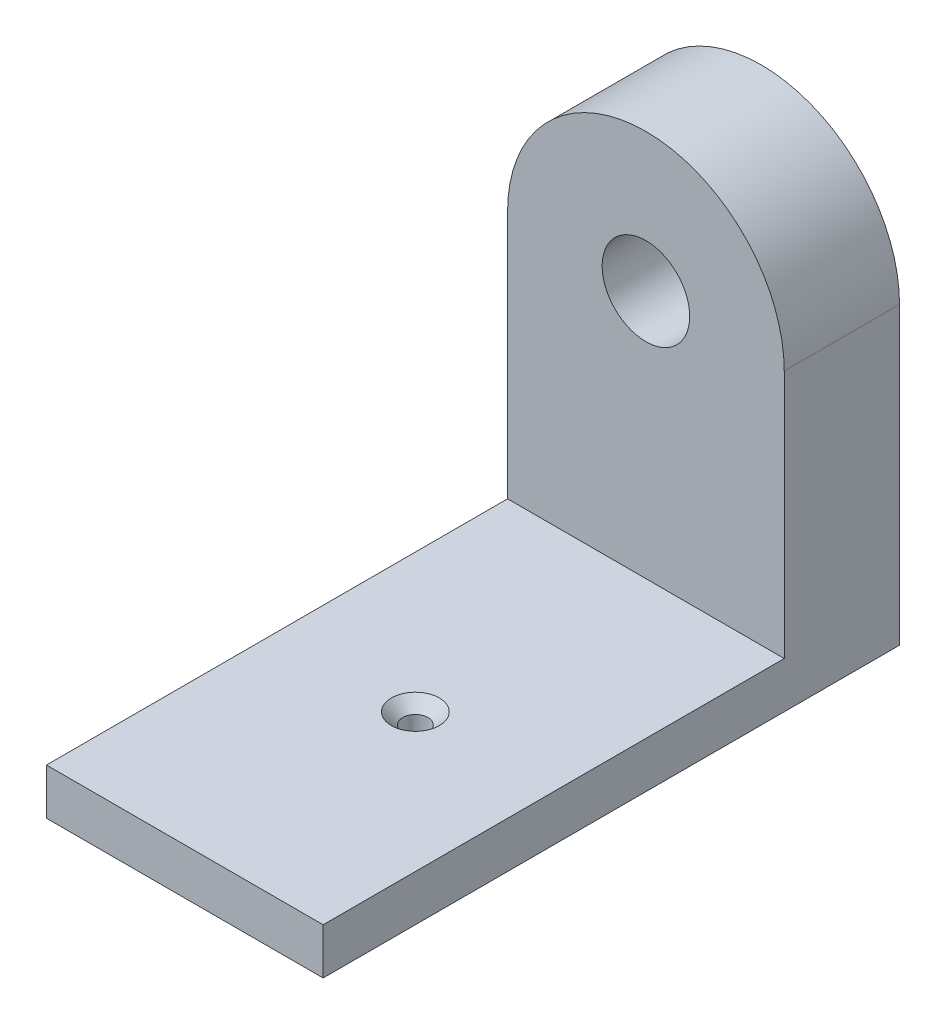
SolidWorks part; units mm, degrees
ref_plane "Front Plane" through (0, 0, 0) normal (0, 0, 1) x (1, 0, 0)
ref_plane "Top Plane" through (0, 0, 0) normal (0, 1, 0) x (1, 0, 0)
ref_plane "Right Plane" through (0, 0, 0) normal (1, 0, 0) x (0, 0, -1)
sketch "Sketch1" plane through (0, 0, 0) normal (0, 1, 0) x (1, 0, 0)
  line L1 (0, 0) -> (60, 0)
  line L2 (0, 0) -> (0, 125)
  line L3 (0, 125) -> (60, 125)
  line L4 (60, 0) -> (60, 125)
  dimension "D1" = 125
  dimension "D2" = 60
extrude "Boss-Extrude1" add sketch "Sketch1" along normal blind 10
sketch "Sketch2" plane through (0, 0, -125) normal (0, 0, -1) x (-1, 0, 0)
  line L0 (-60, 0) -> (0, 0) construction
  line L1 (-60, 10) -> (0, 10)
  line L2 (-60, 10) -> (-60, 64)
  line L3 (0, 10) -> (0, 0) construction
  line L4 (0, 10) -> (0, 64)
  arc A0 (0, 64) -> (-60, 64) centre (-30, 64) ccw
  circle A1 centre (-30, 64) radius 9.5
  dimension "D2" = 19
  dimension "D1" = 64
extrude "Boss-Extrude2" add sketch "Sketch2" against normal blind 25
hole_wizard "CSK for M5 Countersunk Raised Head Screw1" positions "3DSketch3" profile "Sketch7" countersink size "M5" standard "ISO" end condition through all
sketch3d "3DSketch3"
  line L0 (0, 10, -100) -> (0, 10, 0) construction
  line L1 (0, 10, 0) -> (60, 10, 0) construction
  point P0 (30, 10, -50)
  dimension "D1" = 30
  dimension "D2" = 50
sketch "Sketch7" plane through (30, 10, -50) normal (1, 0, 0) x (0, 0, 1)
  line L0 (0, 0) -> (0, 10)
  line L1 (0, 10) -> (2.75, 10)
  line L2 (2.75, 10) -> (2.75, 2.45)
  line L3 (2.75, 2.45) -> (5.2, 0)
  line L5 (5.2, 0) -> (0, 0)
  line L6 (-2.75, 2.45) -> (-5.2, 0) construction
  line L11 (0, -6.35) -> (0, 107.95) construction
  dimension "Thru Hole Dia." = 5.5
  dimension "Thru Hole Depth" = 10
  dimension "Near C'Sink Dia." = 10.4
  dimension "Near C'Sink Angle" = 90
